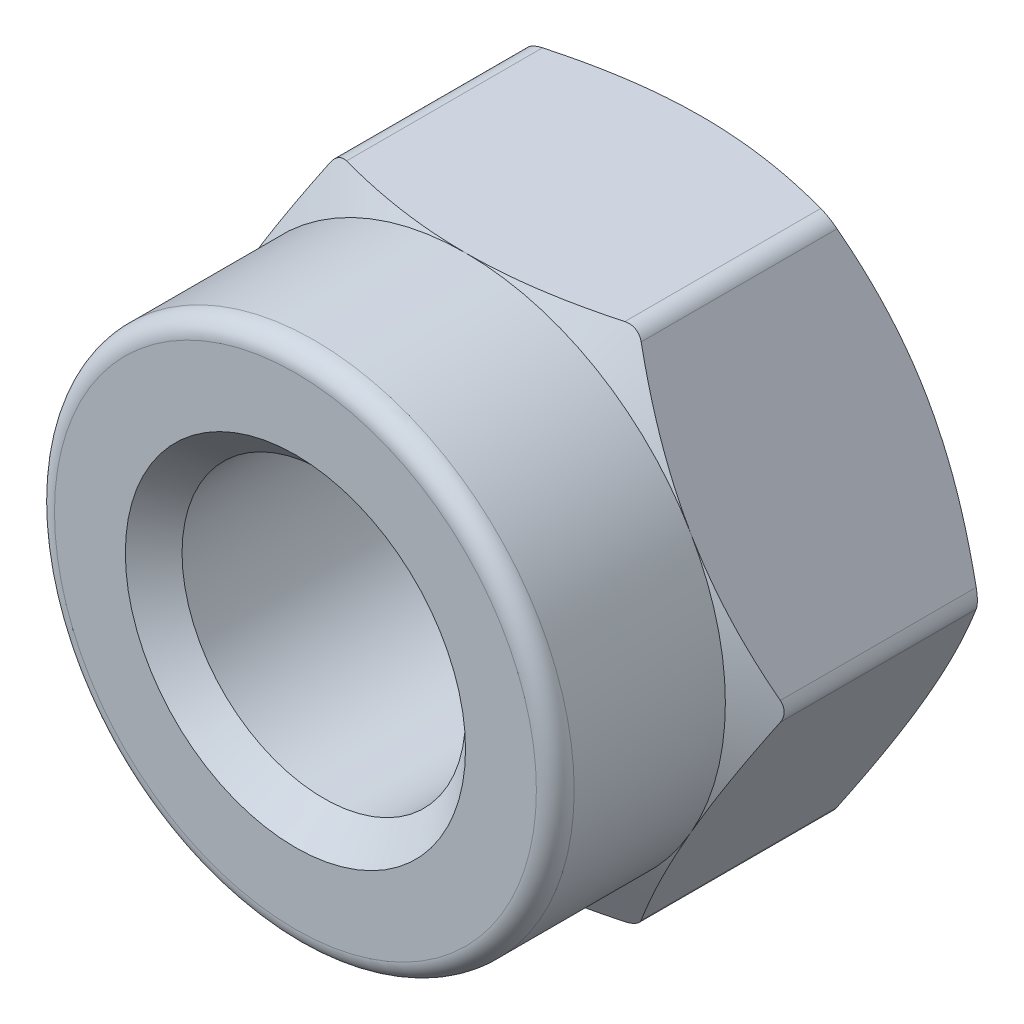
SolidWorks part; units mm, degrees
material "镀铬不锈钢"
ref_plane "前视基准面" through (0, 0, 0) normal (0, 0, 1) x (1, 0, 0)
ref_plane "上视基准面" through (0, 0, 0) normal (0, 1, 0) x (1, 0, 0)
ref_plane "右视基准面" through (0, 0, 0) normal (1, 0, 0) x (0, 0, -1)
sketch "草图1" plane through (0, 0, 0) normal (0, 0, 1) x (1, 0, 0)
  line L1 (3.1754, 0) -> (1.5877, 2.75)
  line L2 (1.5877, 2.75) -> (-1.5877, 2.75)
  line L3 (-1.5877, 2.75) -> (-3.1754, 0)
  line L4 (-3.1754, 0) -> (-1.5877, -2.75)
  line L5 (-1.5877, -2.75) -> (1.5877, -2.75)
  line L6 (1.5877, -2.75) -> (3.1754, 0)
  circle A0 centre (0, 0) radius 2.75 construction
  dimension "D1" = 5.5
extrude "六角高度" add sketch "草图1" along normal blind 2.5
sketch "草图2" plane through (0, 0, 2.5) normal (0, 0, 1) x (1, 0, 0)
  line L0 (1.5877, -2.75) -> (3.1754, 0) construction
  circle A0 centre (0, 0) radius 2.75
extrude "圆柱高度" add sketch "草图2" along normal blind 1.8
sketch "草图3" plane through (0, 0, 4.3) normal (0, 0, 1) x (1, 0, 0)
  circle A0 centre (0, 0) radius 1.5
  dimension "D1" = 3
extrude "内径" cut sketch "草图3" against normal through all
fillet "圆角2" radius 0.2 6 edges at (3.1754, 0, 1.25) (1.5877, 2.75, 1.25) (-1.5877, 2.75, 1.25) (-3.1754, 0, 1.25) (1.5877, -2.75, 1.25) (-1.5877, -2.75, 1.25)
chamfer "倒角1" distance 0.3 angle 45 1 edges at (1.5, 0, 0)
chamfer "倒角2" distance 0.3 angle 45 1 edges at (1.5, 0, 4.3)
sketch "草图5" plane through (0, 0, 0) normal (0, 0, -1) x (-1, 0, 0)
  circle A0 centre (0, 0) radius 2.75
sketch "草图6" plane through (0, 0, 0) normal (0, 1, 0) x (1, 0, 0)
  line L0 (0, 1.9232) -> (0, -5.273) construction
  line L1 (-2.75, 0) -> (-3.1445, -0.2278)
  line L2 (2.75, 0) -> (-2.75, 0) construction
  line L3 (-2.75, 0) -> (-3.1445, 0)
  line L4 (-3.1445, 0) -> (-3.1445, -0.2278)
  line L5 (-7.8764, -1.25) -> (7.2562, -1.25) construction
  line L6 (-3.1445, -2.5) -> (-3.1445, -2.2722)
  line L7 (-2.75, -2.5) -> (-3.1445, -2.5)
  line L8 (-2.75, -2.5) -> (-3.1445, -2.2722)
  line L9 (-3.1177, 0) -> (-3.1177, -2.5) construction
  line L10 (-3.1445, 0) -> (-3.1445, -2.5) construction
  point P16 (-3.1177, -1.25)
  dimension "D1" = 60
revolve "切除-旋转2" cut sketch "草图6" angle 360 about L0
fillet "圆角3" radius 0.2 1 edges at (2.75, 0, 4.3)
